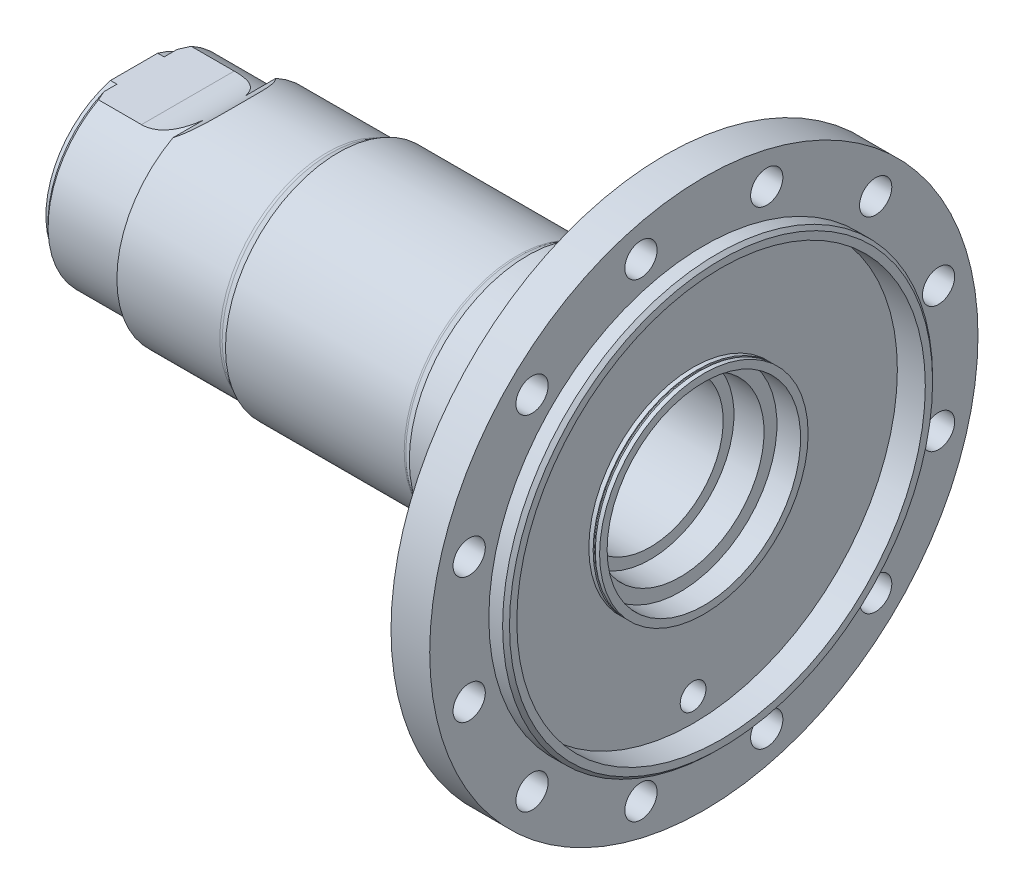
SolidWorks part; units mm, degrees
ref_plane "Спереди" through (0, 0, 0) normal (0, 0, 1) x (1, 0, 0)
ref_plane "Сверху" through (0, 0, 0) normal (0, 1, 0) x (1, 0, 0)
ref_plane "Справа" through (0, 0, 0) normal (1, 0, 0) x (0, 0, -1)
sketch "Эскиз1" plane through (0, 0, 0) normal (0, 0, 1) x (1, 0, 0)
  line L0 (0, 0) -> (273, 0)
  line L1 (0, 0) -> (0, 41)
  line L2 (0, 41) -> (3, 41)
  line L3 (3, 41) -> (3, 43)
  line L4 (3, 43) -> (5, 45)
  line L5 (5, 45) -> (42, 45)
  line L6 (42, 45) -> (42, 50)
  line L7 (42, 50) -> (89.866, 50)
  line L8 (91.366, 50.4019) -> (95, 52.5)
  line L9 (95, 52.5) -> (178.134, 52.5)
  line L10 (179.134, 52.7679) -> (183, 55)
  line L11 (183, 55) -> (213, 55)
  line L12 (215, 57) -> (215, 60.7679)
  line L13 (215, 60.7679) -> (218, 62.5)
  line L14 (218, 62.5) -> (237, 62.5)
  line L15 (239, 64.5) -> (239, 65.5)
  line L16 (239, 65.5) -> (240.4142, 66.9142)
  line L17 (241, 68.3284) -> (241, 78)
  line L18 (241, 78) -> (244.4142, 81.4142)
  line L19 (245, 82.8284) -> (245, 92)
  line L20 (245, 92) -> (246.4142, 93.4142)
  line L21 (247, 94.8284) -> (247, 127.5)
  line L22 (247, 127.5) -> (265, 127.5)
  line L23 (265, 127.5) -> (265, 100)
  line L24 (265, 100) -> (271.4, 100)
  line L25 (271.4, 100) -> (273, 98.4)
  line L26 (273, 98.4) -> (273, 0)
  arc A0 (89.866, 50) -> (91.366, 50.4019) centre (89.866, 53) ccw
  arc A1 (178.134, 52.5) -> (179.134, 52.7679) centre (178.134, 54.5) ccw
  arc A2 (213, 55) -> (215, 57) centre (213, 57) ccw
  arc A3 (237, 62.5) -> (239, 64.5) centre (237, 64.5) ccw
  arc A4 (240.4142, 66.9142) -> (241, 68.3284) centre (239, 68.3284) ccw
  arc A5 (244.4142, 81.4142) -> (245, 82.8284) centre (243, 82.8284) ccw
  arc A6 (246.4142, 93.4142) -> (247, 94.8284) centre (245, 94.8284) ccw
revolve "Повернуть1" add sketch "Эскиз1" angle 360 about L0
sketch "Эскиз2" plane through (0, 0, 0) normal (0, 0, 1) x (1, 0, 0)
  line L0 (0, 0) -> (273, 0)
  line L1 (0, 0) -> (0, 32.7321)
  line L2 (0, 32.7321) -> (3, 31)
  line L3 (3, 31) -> (203.5, 31)
  line L4 (203.5, 31) -> (203.5, 34)
  line L5 (203.5, 34) -> (240, 34)
  line L6 (240, 34) -> (240, 39)
  line L7 (240, 39) -> (254, 39)
  line L8 (254, 39) -> (254, 45)
  line L9 (254, 45) -> (265, 45)
  line L10 (265, 45) -> (265, 95)
  line L11 (265, 95) -> (273, 95)
  line L12 (273, 95) -> (273, 0)
revolve "Вырез-Повернуть1" cut sketch "Эскиз2" angle 360 about L0
sketch "Эскиз3" plane through (0, 0, 0) normal (0, 0, 1) x (1, 0, 0)
  line L0 (0, 0) -> (273, 0) construction
  line L1 (260, 48.5) -> (262, 48.5)
  line L2 (262, 48.5) -> (262, 95)
  line L3 (262, 95) -> (260, 95)
  line L4 (260, 95) -> (260, 48.5)
revolve "Rear_recess_left" cut sketch "Эскиз3" angle 360 about L0
sketch "Эскиз4" plane through (0, 0, 0) normal (0, 0, 1) x (1, 0, 0)
  line L0 (0, 0) -> (273, 0) construction
  line L1 (263, 48) -> (263, 95)
  line L2 (263, 95) -> (262, 95)
  line L3 (262, 95) -> (262, 48)
  arc A0 (262, 48) -> (262.5, 47.5) centre (262.5, 48) ccw
  arc A1 (262.5, 47.5) -> (263, 48) centre (262.5, 48) ccw
revolve "Collar_groove_nominal" cut sketch "Эскиз4" angle 360 about L0
sketch "Эскиз5" plane through (0, 0, 0) normal (0, 0, 1) x (1, 0, 0)
  line L0 (0, 0) -> (273, 0) construction
  line L1 (263, 48.5) -> (265, 48.5)
  line L2 (265, 48.5) -> (265, 95)
  line L3 (265, 95) -> (263, 95)
  line L4 (263, 95) -> (263, 48.5)
revolve "Rear_recess_lip" cut sketch "Эскиз5" angle 360 about L0
sketch "Эскиз6" plane through (0, 0, 0) normal (1, 0, 0) x (0, 0, -1)
  circle A0 centre (109.1496, 29.2466) radius 7.5
extrude "Вырез-Вытянуть1" cut sketch "Эскиз6" along normal through all
sketch "Эскиз7" plane through (0, 0, 0) normal (1, 0, 0) x (0, 0, -1)
  circle A0 centre (79.9031, 79.9031) radius 7.5
extrude "Вырез-Вытянуть2" cut sketch "Эскиз7" along normal through all
sketch "Эскиз8" plane through (0, 0, 0) normal (1, 0, 0) x (0, 0, -1)
  circle A0 centre (29.2466, 109.1496) radius 7.5
extrude "Вырез-Вытянуть3" cut sketch "Эскиз8" along normal through all
sketch "Эскиз9" plane through (0, 0, 0) normal (1, 0, 0) x (0, 0, -1)
  circle A0 centre (-29.2466, 109.1496) radius 7.5
extrude "Вырез-Вытянуть4" cut sketch "Эскиз9" along normal through all
sketch "Эскиз10" plane through (0, 0, 0) normal (1, 0, 0) x (0, 0, -1)
  circle A0 centre (-79.9031, 79.9031) radius 7.5
extrude "Вырез-Вытянуть5" cut sketch "Эскиз10" along normal through all
sketch "Эскиз11" plane through (0, 0, 0) normal (1, 0, 0) x (0, 0, -1)
  circle A0 centre (-109.1496, 29.2466) radius 7.5
extrude "Вырез-Вытянуть6" cut sketch "Эскиз11" along normal through all
sketch "Эскиз12" plane through (0, 0, 0) normal (1, 0, 0) x (0, 0, -1)
  circle A0 centre (-109.1496, -29.2466) radius 7.5
extrude "Вырез-Вытянуть7" cut sketch "Эскиз12" along normal through all
sketch "Эскиз13" plane through (0, 0, 0) normal (1, 0, 0) x (0, 0, -1)
  circle A0 centre (-79.9031, -79.9031) radius 7.5
extrude "Вырез-Вытянуть8" cut sketch "Эскиз13" along normal through all
sketch "Эскиз14" plane through (0, 0, 0) normal (1, 0, 0) x (0, 0, -1)
  circle A0 centre (-29.2466, -109.1496) radius 7.5
extrude "Вырез-Вытянуть9" cut sketch "Эскиз14" along normal through all
sketch "Эскиз15" plane through (0, 0, 0) normal (1, 0, 0) x (0, 0, -1)
  circle A0 centre (29.2466, -109.1496) radius 7.5
extrude "Вырез-Вытянуть10" cut sketch "Эскиз15" along normal through all
sketch "Эскиз16" plane through (0, 0, 0) normal (1, 0, 0) x (0, 0, -1)
  circle A0 centre (79.9031, -79.9031) radius 7.5
extrude "Вырез-Вытянуть11" cut sketch "Эскиз16" along normal through all
sketch "Эскиз17" plane through (0, 0, 0) normal (1, 0, 0) x (0, 0, -1)
  circle A0 centre (109.1496, -29.2466) radius 7.5
extrude "Вырез-Вытянуть12" cut sketch "Эскиз17" along normal through all
sketch "Эскиз18" plane through (0, 0, 0) normal (1, 0, 0) x (0, 0, -1)
  circle A0 centre (0, -84) radius 6
extrude "Вырез-Вытянуть13" cut sketch "Эскиз18" along normal through all
sketch "Эскиз19" plane through (0, 0, 0) normal (0, 0, 1) x (1, 0, 0)
  line L0 (-1, 39.5) -> (25, 39.5)
  line L1 (60, 74.5) -> (60, 150)
  line L2 (60, 150) -> (-1, 150)
  line L3 (-1, 150) -> (-1, 39.5)
  arc A0 (25, 39.5) -> (60, 74.5) centre (25, 74.5) ccw
extrude "Left_flat_84_5_R35" cut sketch "Эскиз19" against normal through all and the other way through all
sketch "Эскиз20" plane through (0, 0, 0) normal (0, 0, 1) x (1, 0, 0)
  line L0 (-1, -25) -> (3, -25)
  line L1 (3, -25) -> (3, -100)
  line L2 (3, -100) -> (-1, -100)
  line L3 (-1, -100) -> (-1, -25)
extrude "Left_end_bottom_20" cut sketch "Эскиз20" against normal through all and the other way through all
